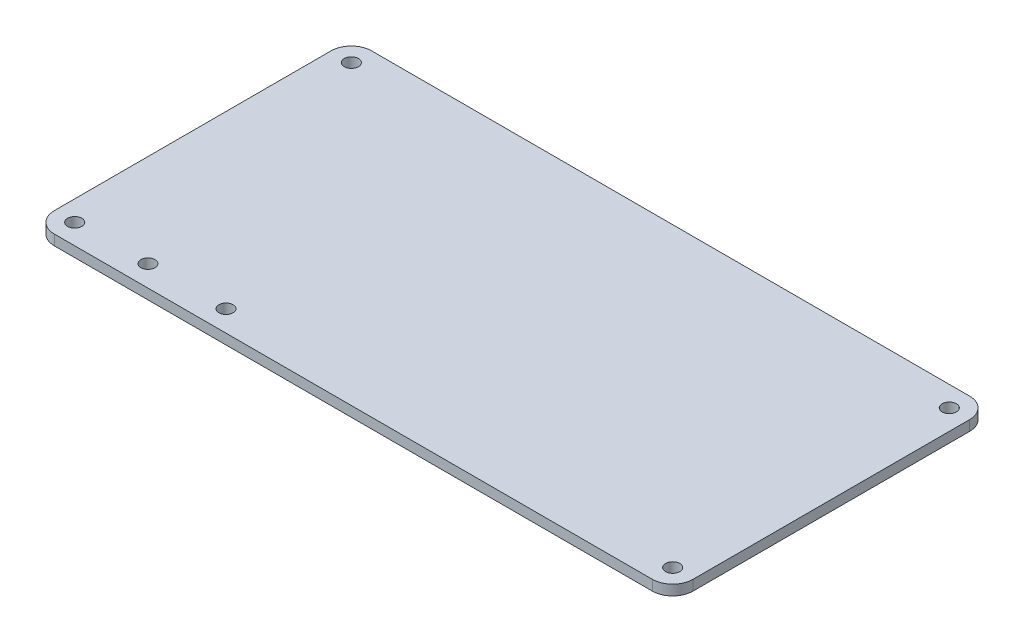
SolidWorks part; units mm, degrees
ref_plane "Front Plane" through (0, 0, 0) normal (0, 0, 1) x (1, 0, 0)
ref_plane "Top Plane" through (0, 0, 0) normal (0, 1, 0) x (1, 0, 0)
ref_plane "Right Plane" through (0, 0, 0) normal (1, 0, 0) x (0, 0, -1)
sketch "Sketch1" plane through (0, 0, 0) normal (0, 1, 0) x (1, 0, 0)
  line L0 (49.8475, 0) -> (49.8475, 49.53) construction
  line L1 (3.175, 0) -> (96.52, 0)
  line L2 (0, 3.175) -> (0, 46.355)
  line L3 (3.175, 49.53) -> (96.52, 49.53)
  line L4 (99.695, 3.175) -> (99.695, 46.355)
  line L5 (49.8475, 24.765) -> (0, 24.765) construction
  circle A0 centre (3.175, 46.355) radius 1.1112
  circle A1 centre (3.175, 46.355) radius 2.2225 construction
  arc A2 (3.175, 49.53) -> (0, 46.355) centre (3.175, 46.355) ccw
  circle A3 centre (96.52, 46.355) radius 1.1113
  circle A4 centre (96.52, 46.355) radius 2.2225 construction
  arc A5 (96.52, 49.53) -> (99.695, 46.355) centre (96.52, 46.355) cw
  circle A6 centre (96.52, 3.175) radius 1.1113
  circle A7 centre (96.52, 3.175) radius 2.2225 construction
  arc A8 (96.52, 0) -> (99.695, 3.175) centre (96.52, 3.175) ccw
  arc A9 (3.175, 0) -> (0, 3.175) centre (3.175, 3.175) cw
  circle A10 centre (3.175, 3.175) radius 2.2225 construction
  circle A11 centre (3.175, 3.175) radius 1.1112
  dimension "D4" = 3.175
  dimension "D5" = 4.445
  dimension "D1" = 2.2225
  dimension "D3" = 3.175
extrude "Boss-Extrude1" add sketch "Sketch1" along normal blind 1.6
sketch "Sketch2" plane through (0, 1.6, 0) normal (0, 1, 0) x (1, 0, 0)
  line L0 (3.175, 0) -> (96.52, 0) construction
  circle A0 centre (14.4785, 3.302) radius 1.1
  circle A1 centre (26.6685, 3.302) radius 1.1
  dimension "D1" = 2.2
  dimension "D2" = 2.2
  dimension "D4" = 3.302
  dimension "D3" = 12.19
extrude "Cut-Extrude1" cut sketch "Sketch2" against normal through all
